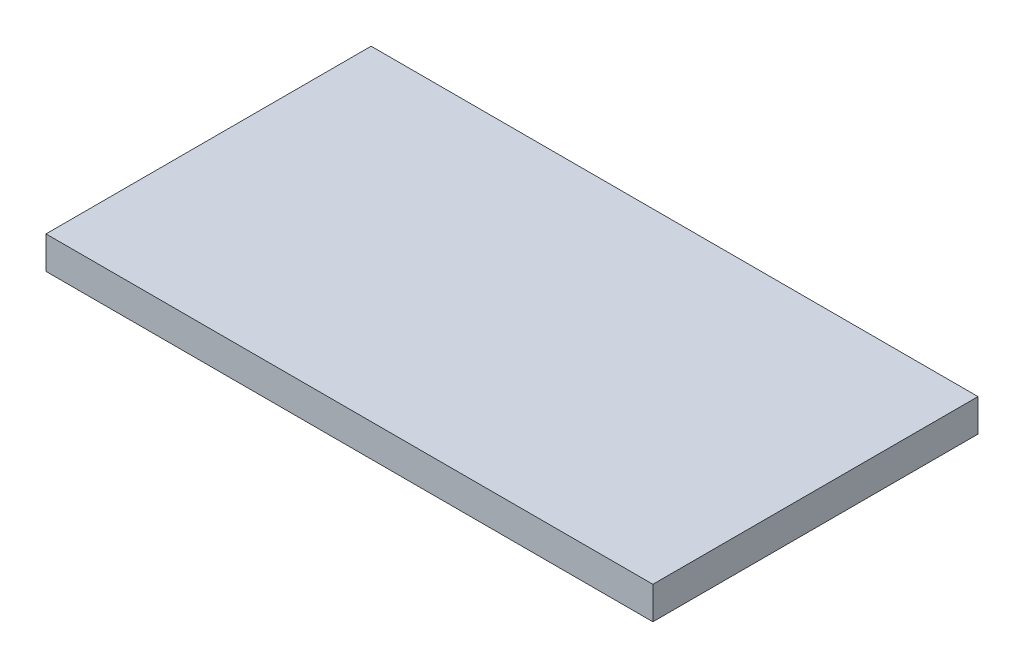
SolidWorks part; units mm, degrees
material "Maple"
ref_plane "Front Plane" through (0, 0, 0) normal (0, 0, 1) x (1, 0, 0)
ref_plane "Top Plane" through (0, 0, 0) normal (0, 1, 0) x (1, 0, 0)
ref_plane "Right Plane" through (0, 0, 0) normal (1, 0, 0) x (0, 0, -1)
sketch "Sketch1" plane through (0, 0, 0) normal (0, 1, 0) x (1, 0, 0)
  line L1 (0, 0) -> (1422.4, 0)
  line L2 (0, 0) -> (0, 762)
  line L3 (0, 762) -> (1422.4, 762)
  line L4 (1422.4, 0) -> (1422.4, 762)
  dimension "D1" = 762
  dimension "D2" = 1422.4
extrude "Boss-Extrude1" add sketch "Sketch1" along normal blind 76.2
sketch "Sketch3" plane through (0, 0, 0) normal (0, -1, 0) x (1, 0, 0)
  line L1 (101.6, -152.4) -> (203.2, -152.4)
  line L2 (101.6, -152.4) -> (101.6, -50.8)
  line L3 (101.6, -50.8) -> (203.2, -50.8)
  line L4 (203.2, -152.4) -> (203.2, -50.8)
  line L5 (101.6, -609.6) -> (203.2, -609.6)
  line L6 (101.6, -609.6) -> (101.6, -711.2)
  line L7 (101.6, -711.2) -> (203.2, -711.2)
  line L8 (203.2, -609.6) -> (203.2, -711.2)
  line L9 (1219.2, -50.8) -> (1320.8, -50.8)
  line L10 (1219.2, -50.8) -> (1219.2, -152.4)
  line L11 (1219.2, -152.4) -> (1320.8, -152.4)
  line L12 (1320.8, -50.8) -> (1320.8, -152.4)
  line L13 (1219.2, -609.6) -> (1320.8, -609.6)
  line L14 (1219.2, -609.6) -> (1219.2, -711.2)
  line L15 (1219.2, -711.2) -> (1320.8, -711.2)
  line L16 (1320.8, -609.6) -> (1320.8, -711.2)
  line L17 (0, 0) -> (1422.4, 0) construction
  line L18 (0, -762) -> (0, 0) construction
  line L19 (1422.4, -762) -> (0, -762) construction
  line L20 (1422.4, 0) -> (1422.4, -762) construction
  dimension "D1" = 101.6
  dimension "D2" = 101.6
  dimension "D3" = 101.6
  dimension "D4" = 101.6
  dimension "D5" = 101.6
  dimension "D6" = 101.6
  dimension "D7" = 101.6
  dimension "D8" = 101.6
  dimension "D9" = 50.8
  dimension "D10" = 101.6
  dimension "D11" = 101.6
  dimension "D12" = 50.8
  dimension "D13" = 50.8
  dimension "D14" = 101.6
  dimension "D15" = 101.6
  dimension "D16" = 50.8
extrude "Cut-Extrude1" cut sketch "Sketch3" against normal blind 38.1
